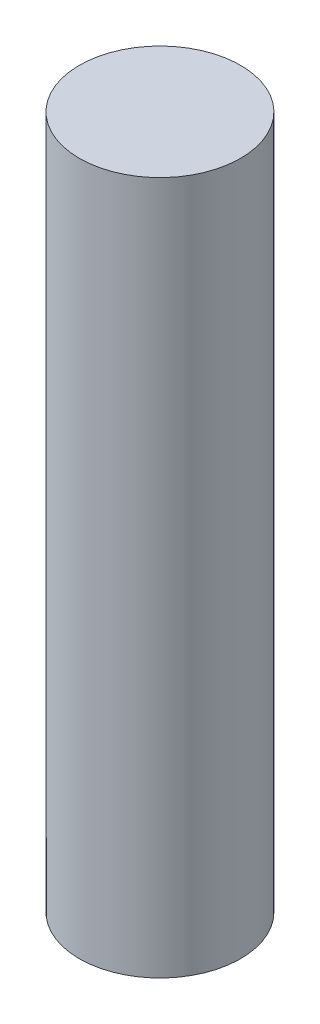
SolidWorks part; units mm, degrees
material "1023 Carbon Steel Sheet (SS)"
ref_plane "Front Plane" through (0, 0, 0) normal (0, 0, 1) x (1, 0, 0)
ref_plane "Top Plane" through (0, 0, 0) normal (0, 1, 0) x (1, 0, 0)
ref_plane "Right Plane" through (0, 0, 0) normal (1, 0, 0) x (0, 0, -1)
sketch "Sketch1" plane through (0, 0, 0) normal (0, 1, 0) x (1, 0, 0)
  circle A0 centre (0, 0) radius 5
  dimension "D1" = 10
extrude "Boss-Extrude1" add sketch "Sketch1" along normal blind 43
